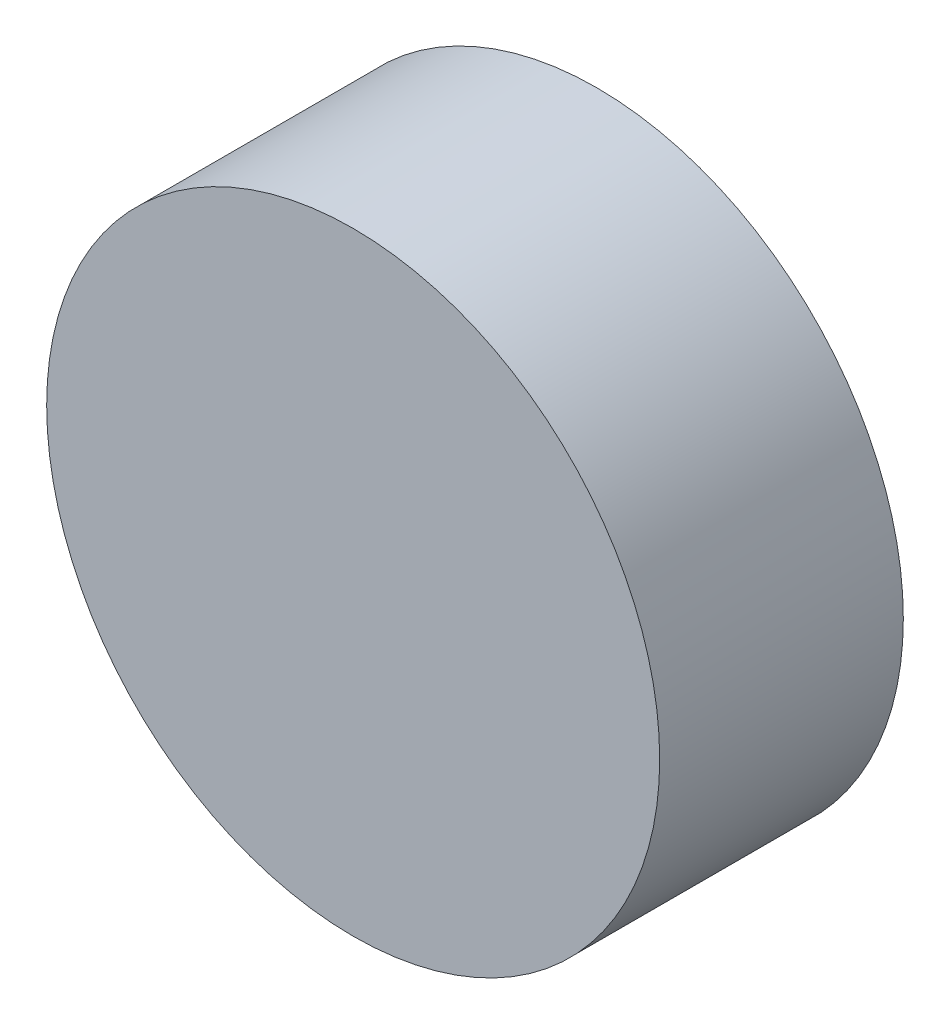
SolidWorks part; units mm, degrees
ref_plane "Front Plane" through (0, 0, 0) normal (0, 0, 1) x (1, 0, 0)
ref_plane "Top Plane" through (0, 0, 0) normal (0, 1, 0) x (1, 0, 0)
ref_plane "Right Plane" through (0, 0, 0) normal (1, 0, 0) x (0, 0, -1)
sketch "Sketch1" plane through (0, 0, 0) normal (0, 0, 1) x (1, 0, 0)
  circle A0 centre (0, 0) radius 29
  dimension "D1" = 58
extrude "Boss-Extrude1" add sketch "Sketch1" along normal blind 23.0502
sketch "Sketch2" plane through (0, 0, 0) normal (0, 0, 1) x (1, 0, 0)
  line L0 (0, 29) -> (0, -29) construction
  line L1 (-29, 0) -> (29, 0) construction
  circle A0 centre (0, 0) radius 29 construction
sketch "Sketch3" plane through (0, 0, 0) normal (0, 0, -1) x (-1, 0, 0)
  point P0 (0, 0)
